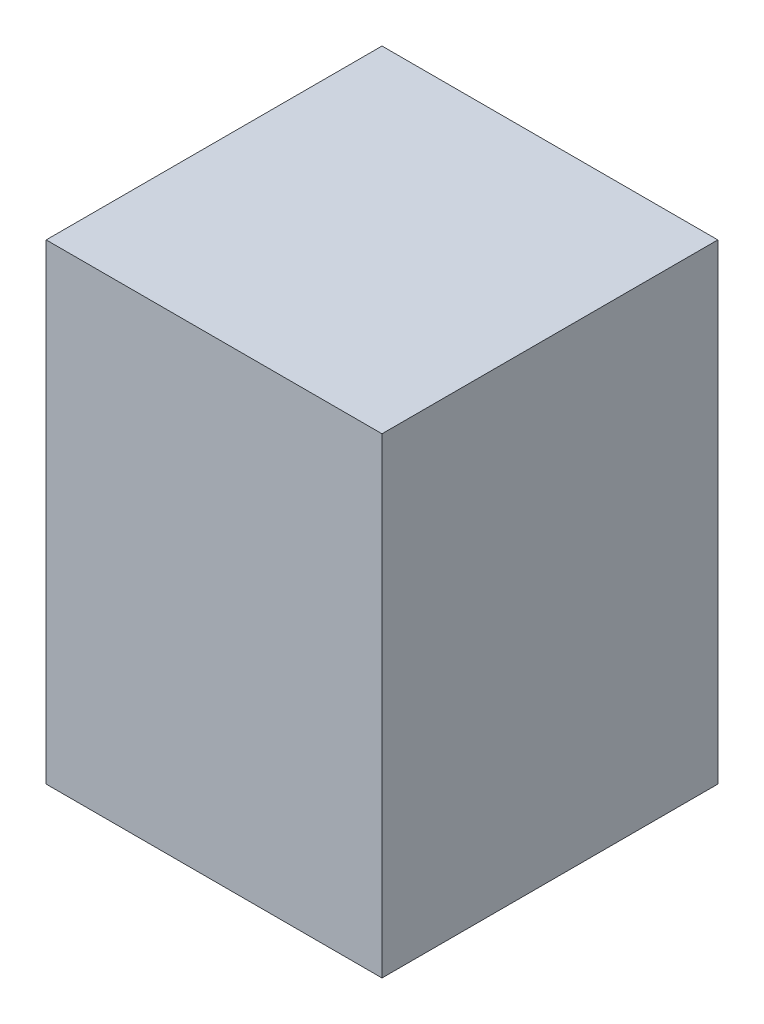
SolidWorks part; units mm, degrees
ref_plane "Front Plane" through (0, 0, 0) normal (0, 0, 1) x (1, 0, 0)
ref_plane "Top Plane" through (0, 0, 0) normal (0, 1, 0) x (1, 0, 0)
ref_plane "Right Plane" through (0, 0, 0) normal (1, 0, 0) x (0, 0, -1)
other "Configuration Table"
sketch "Sketch1" plane through (0, 0, 0) normal (0, 0, 1) x (1, 0, 0)
  line L1 (322, 300) -> (379, 300)
  line L2 (322, 300) -> (322, 380)
  line L3 (322, 380) -> (379, 380)
  line L4 (379, 300) -> (379, 380)
extrude "PACK_step_motor_NEMA23_3Nm_1" add sketch "Sketch1" against normal blind 57 from offset 373 separate body
